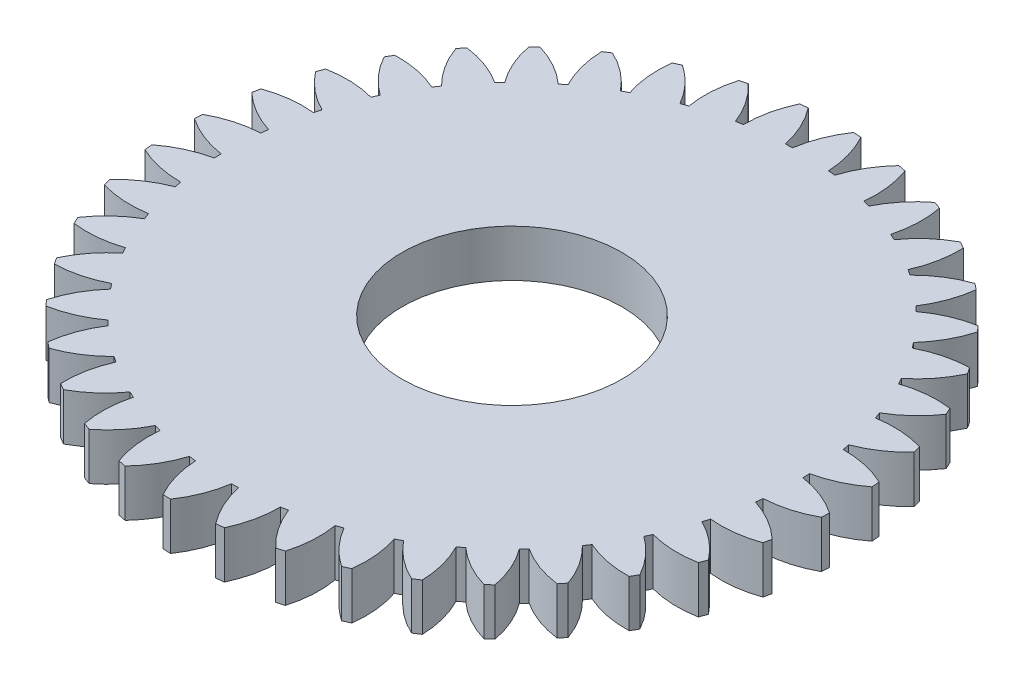
SolidWorks part; units mm, degrees
ref_plane "Alzado" through (0, 0, 0) normal (0, 0, 1) x (1, 0, 0)
ref_plane "Planta" through (0, 0, 0) normal (0, 1, 0) x (1, 0, 0)
ref_plane "Vista lateral" through (0, 0, 0) normal (1, 0, 0) x (0, 0, -1)
sketch "Croquis1" plane through (0, 0, 0) normal (0, 1, 0) x (1, 0, 0)
  line L0 (0, 0) -> (0, 16.4937) construction
  line L1 (0, 0) -> (5.8581, 16.095) construction
  line L2 (0, 9.75) -> (3.1336, 8.6095) construction
  line L3 (0, 0) -> (-0.5, 16.4937) construction
  circle A4 centre (0, 0) radius 10.5
  circle A5 centre (0, 0) radius 9.1
  circle A6 centre (0, 0) radius 9.75
  circle A7 centre (3.1336, 8.6095) radius 3.3347
  circle A8 centre (-3.6493, 8.4038) radius 3.3347
  dimension "D1" = 21
  dimension "D2" = 18.2
  dimension "D3" = 19.5
  dimension "D4" = 20
  dimension "D5" = 0.5
sketch "Croquis2" plane through (0, 0, 0) normal (0, 1, 0) x (1, 0, 0)
  circle A0 centre (0, 0) radius 10.5
  circle A1 centre (0, 0) radius 3.5
  dimension "D1" = 7
  dimension "D2" = 21
extrude "Saliente-Extruir1" add sketch "Croquis2" along normal blind 1.5
extrude "Cortar-Extruir1" cut sketch "Croquis1" along normal blind 16 contours A4 A8 A6 A7 | A6 A8 A5 A7
pattern_circular "MatrizC1" count 40 over 360 about axis through (0, 0, 0) along (0, 1, 0) of "Cortar-Extruir1"
